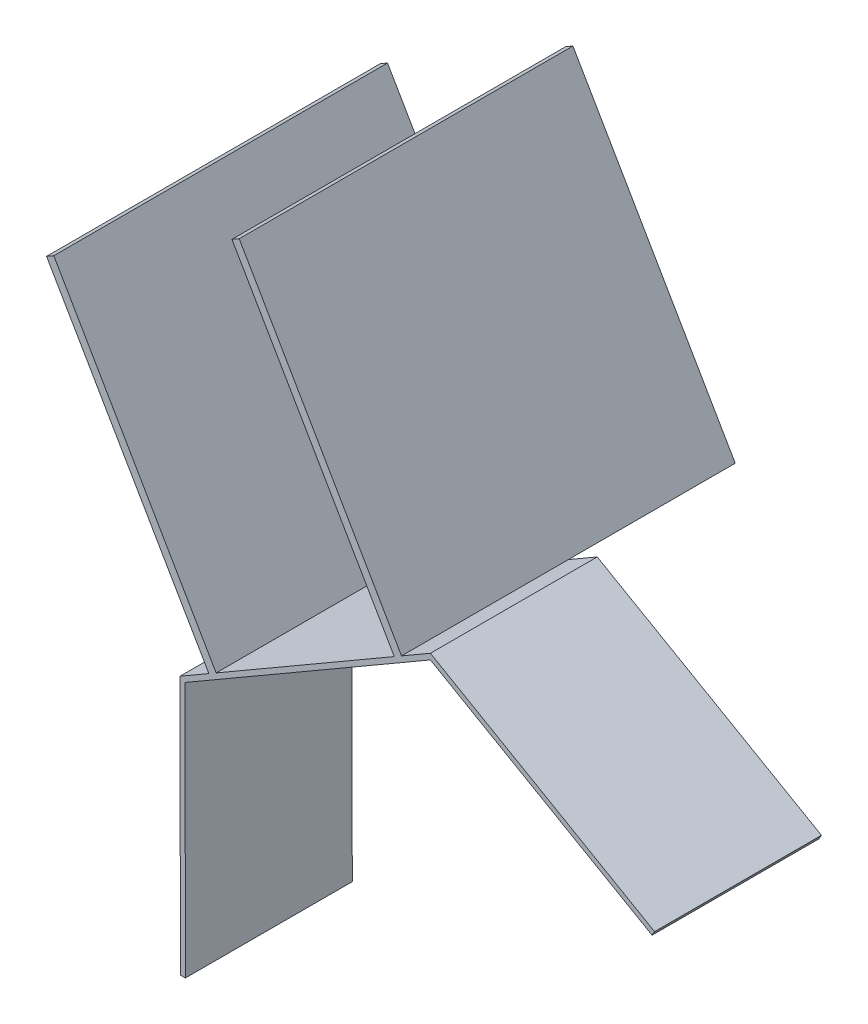
SolidWorks part; units mm, degrees
ref_plane "Front Plane" through (0, 0, 0) normal (0, 0, 1) x (1, 0, 0)
ref_plane "Top Plane" through (0, 0, 0) normal (0, 1, 0) x (1, 0, 0)
ref_plane "Right Plane" through (0, 0, 0) normal (1, 0, 0) x (0, 0, -1)
sketch "Sketch1" plane through (0, 0, 0) normal (0, 0, 1) x (1, 0, 0)
  line L0 (1528.9664, 0) -> (0, 0) construction
  line L1 (0, 0) -> (-918.1607, 1590.301) construction
  line L2 (0, 0) -> (-694.8278, -1203.4771) construction
  line L3 (0, 0) -> (-1542.2771, 0) construction
  line L4 (0, 0) -> (625.4451, 1083.3028) construction
  line L5 (0, 0) -> (646.494, -1119.7604) construction
  line L6 (-1000, 0) -> (-502.6514, 864.4892)
  line L7 (-502.6514, 864.4892) -> (502.6514, 864.4892)
  line L8 (502.6514, 864.4892) -> (1000, 0)
  line L9 (1000, 0) -> (500, -866.0254)
  line L10 (500, -866.0254) -> (-500, -866.0254)
  line L11 (-500, -866.0254) -> (-1000, 0)
  line L12 (1224.9953, 228.0643) -> (1224.9953, -221.9357)
  line L13 (-810.0072, 946.8449) -> (-420.2957, 1171.8449)
  line L14 (-810.0072, 946.8449) -> (-585.0072, 557.1335)
  line L15 (-585.0072, 557.1335) -> (-195.2957, 782.1335)
  line L16 (-420.2957, 1171.8449) -> (-195.2957, 782.1335)
  line L17 (-810.0072, 946.8449) -> (-195.2957, 782.1335) construction
  line L18 (-585.0072, 557.1335) -> (-420.2957, 1171.8449) construction
  line L19 (-500, -866.0254) -> (-502.6514, 864.4892)
  line L20 (-502.6514, 864.4892) -> (1000, 0)
  line L21 (1000, 0) -> (-500, -866.0254)
  line L22 (-599.9999, -866.1786) -> (-602.6563, 867.5995)
  line L23 (-946.6097, 983.4474) -> (-58.6932, 745.5309) construction
  line L24 (-455.6168, 952.7978) -> (1049.8673, 86.679)
  line L25 (1050, -86.6025) -> (-450, -952.6279)
  line L26 (-602.6513, 864.336) -> (-502.6514, 864.4892)
  line L27 (1224.9953, -221.9357) -> (774.9953, -221.9357)
  line L28 (774.9953, 228.0643) -> (774.9953, -221.9357)
  line L29 (-452.7842, 951.1682) -> (-502.6514, 864.4892)
  line L30 (1224.9953, 228.0643) -> (774.9953, 228.0643)
  line L31 (1049.8673, 86.679) -> (1000, 0)
  line L32 (-414.9882, -1174.9092) -> (-804.6996, -949.9092)
  line L33 (1000, 0) -> (1050, -86.6025)
  line L34 (-450, -952.6279) -> (-500, -866.0254)
  line L35 (-804.6996, -949.9092) -> (-579.6996, -560.1978)
  line L36 (-189.9882, -785.1978) -> (-579.6996, -560.1978)
  line L37 (-599.9999, -866.1786) -> (-500, -866.0254)
  line L38 (-414.9882, -1174.9092) -> (-189.9882, -785.1978)
  line L39 (-602.9953, -869.1832) -> (-499.9954, -869.0254)
  line L40 (-602.9999, -866.1832) -> (-605.659, 869.3269)
  line L41 (-602.9999, -866.1832) -> (-605.6513, 864.3314) construction
  line L42 (-451.2882, 953.7686) -> (1051.3633, 89.2794)
  line L43 (-602.9953, -869.1832) -> (-605.6559, 867.3314) construction
  line L44 (-605.6559, 867.3314) -> (-502.656, 867.4892) construction
  line L45 (-451.2882, 953.7686) -> (-455.6221, 956.262)
  line L46 (-605.659, 869.3269) -> (-455.6221, 956.262)
  line L47 (-602.6563, 867.5995) -> (-455.6168, 952.7978)
  line L48 (-602.4215, 714.3314) -> (-605.4215, 714.3314)
  line L49 (-322.7656, 876.3673) -> (-321.2696, 878.9677)
  line L50 (-599.9999, -866.1786) -> (-602.6513, 864.336) construction
  line L51 (-452.7842, 951.1682) -> (1049.8673, 86.679) construction
  line L52 (-604.1473, 866.7356) -> (-454.1181, 953.6662) construction
  line L53 (-605.6513, 869.3314) -> (-455.6221, 956.262) construction
  circle A0 centre (0, 0) radius 750 construction
  circle A1 centre (0, 0) radius 1000 construction
  point P31 (0, 0)
  point P32 (-18.2945, 0.0494)
  point P45 (0, 0)
  dimension "D1" = 1500
  dimension "D2" = 2000
  dimension "D3" = 120
  dimension "D4" = 1005.3029
  dimension "D5" = 60
  dimension "D6" = 60
  dimension "D7" = 60
  dimension "D8" = 450
  dimension "D9" = 100
  dimension "D11" = 60
  dimension "D12" = 3
  dimension "D10" = 3
  dimension "D14" = 3
  dimension "D17" = 150
  dimension "D18" = 3
  dimension "D13" = 3
extrude "Boss-Extrude3" add sketch "Sketch1" along normal mid plane 100
sketch "Sketch3" plane through (-529.3341, 913.5514, 0) normal (-0.5013, 0.8652, 0) x (0.8652, 0.5013, 0)
  line L0 (-88.2116, -50) -> (85.1918, -50) construction
  line L1 (65.1918, 150) -> (60.1918, 150)
  line L2 (65.1918, 150) -> (65.1918, -50)
  line L3 (65.1918, -50) -> (60.1918, -50)
  line L4 (60.1918, 150) -> (60.1918, -50)
  line L5 (85.1918, -50) -> (85.1918, 50) construction
  line L6 (-68.2116, 150) -> (-63.2116, 150)
  line L7 (-68.2116, 150) -> (-68.2116, -50)
  line L8 (-68.2116, -50) -> (-63.2116, -50)
  line L9 (-63.2116, 150) -> (-63.2116, -50)
  line L10 (-88.2116, -50) -> (-88.2116, 50) construction
  point P4 (0, 0)
  point P11 (0, 0)
  dimension "D1" = 5
  dimension "D2" = 20
  dimension "D3" = 20
extrude "Boss-Extrude4" add sketch "Sketch3" along normal blind 194.04
